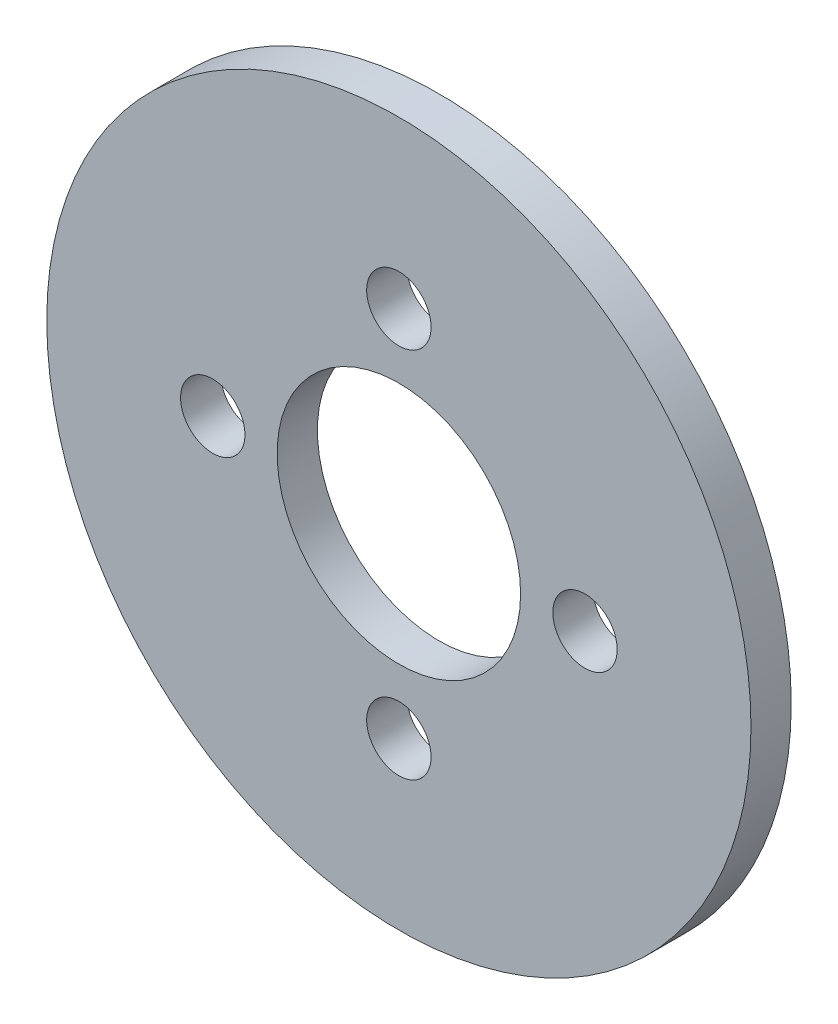
SolidWorks part; units mm, degrees
ref_plane "正面" through (0, 0, 0) normal (0, 0, 1) x (1, 0, 0)
ref_plane "平面" through (0, 0, 0) normal (0, 1, 0) x (1, 0, 0)
ref_plane "右側面" through (0, 0, 0) normal (1, 0, 0) x (0, 0, -1)
sketch "ｽｹｯﾁ1" plane through (0, 0, 0) normal (0, 0, 1) x (1, 0, 0)
  line L1 (9.25, 0) -> (0, 9.25) construction
  line L2 (0, 9.25) -> (-9.25, 0) construction
  line L3 (-9.25, 0) -> (0, -9.25) construction
  line L4 (0, -9.25) -> (9.25, 0) construction
  circle A0 centre (0, 0) radius 17.5
  circle A1 centre (0, 0) radius 6.5407 construction
  circle A2 centre (0, 9.25) radius 1.6
  circle A3 centre (9.25, 0) radius 1.6
  circle A4 centre (-9.25, 0) radius 1.6
  circle A5 centre (0, -9.25) radius 1.6
  circle A6 centre (0, 0) radius 6.05
  dimension "D1" = 35
  dimension "D3" = 3.2
  dimension "D4" = 3.2
  dimension "D5" = 3.2
  dimension "D6" = 3.2
  dimension "D7" = 12.1
  dimension "D2" = 18.5
extrude "ﾎﾞｽ - 押し出し1" add sketch "ｽｹｯﾁ1" along normal blind 2
